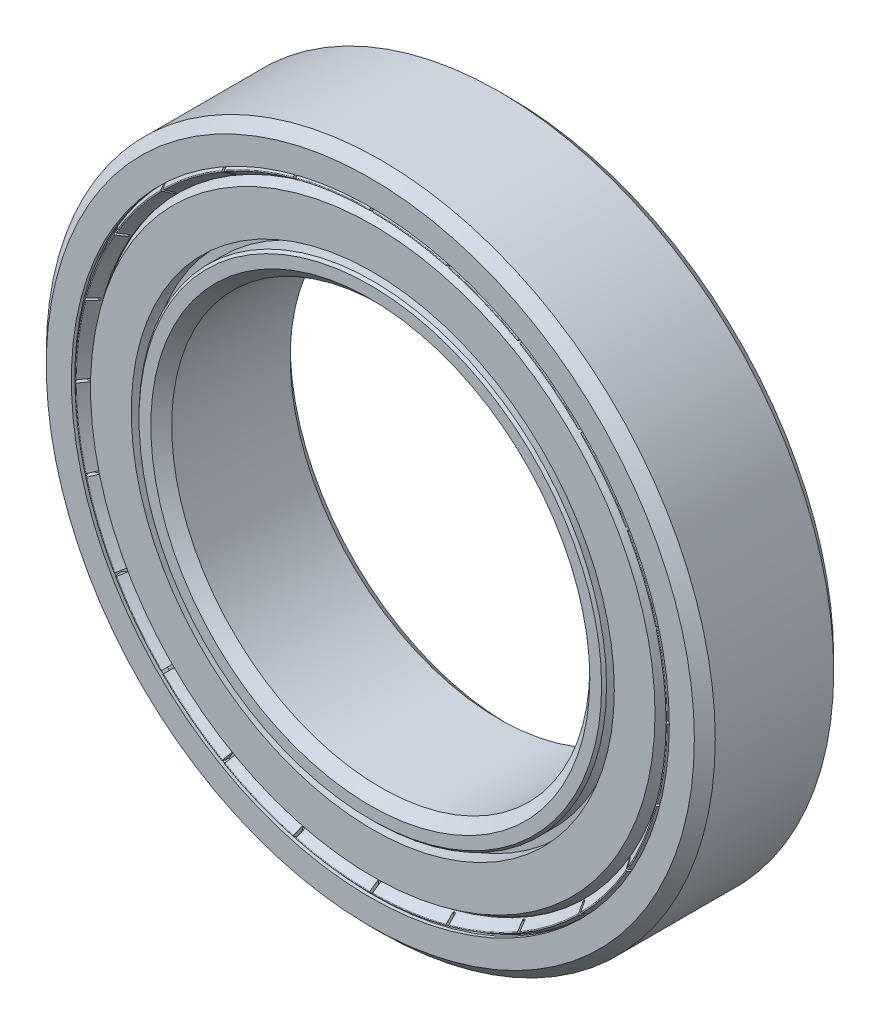
SolidWorks part; units mm, degrees
ref_plane "Front Plane" through (0, 0, 0) normal (0, 0, 1) x (1, 0, 0)
ref_plane "Top Plane" through (0, 0, 0) normal (0, 1, 0) x (1, 0, 0)
ref_plane "Right Plane" through (0, 0, 0) normal (1, 0, 0) x (0, 0, -1)
sketch "Sketch1" plane through (0, 0, 0) normal (0, 0, 1) x (1, 0, 0)
  circle A0 centre (0, 0) radius 7.5
  circle A1 centre (0, 0) radius 12
  dimension "OD" = 24
  dimension "ID" = 15
sketch "Sketch2" plane through (0, 0, 0) normal (1, 0, 0) x (0, 0, -1)
  line L0 (-2.5, 12) -> (2.5, 12)
  line L1 (-2.5, 7.5) -> (-2.5, -7.5) construction
  line L2 (2.5, 12) -> (2.5, -12) construction
  line L3 (-2.5, 0) -> (2.5, 0) construction
  line L6 (0, 12) -> (0, 7.5) construction
  circle A0 centre (0, 9.75) radius 1.575 construction
  point P8 (0, 12)
  dimension "Approx. Ball Dia." = 3.15
  dimension "Width" = 5
  dimension "For Shaft Diameter" = 15
  dimension "For Housing ID" = 24
sketch "Sketch3" plane through (0, 0, 0) normal (1, 0, 0) x (0, 0, -1)
  line L0 (0, 0) -> (0, 15) construction
  line L1 (-2.5, 7.5) -> (-2.5, -7.5) construction
  line L2 (2.125, 12) -> (-2.125, 12)
  line L3 (-2.125, 12) -> (-2.5, 11.625)
  line L4 (-2.5, 11.625) -> (-2.5, 10.7262)
  line L5 (-2.5, 10.7262) -> (-2.375, 10.7262)
  line L6 (-2.375, 10.7262) -> (-2.375, 11.0256)
  line L7 (-2.375, 11.0256) -> (-2.2866, 11.114)
  line L8 (-2.2866, 11.114) -> (-0.7875, 11.114)
  line L10 (-2.5, 12) -> (2.5, 12) construction
  line L12 (-2.375, 11.0256) -> (-2.375, 11.325) construction
  line L13 (2.2866, 11.114) -> (0.7875, 11.114)
  line L14 (2.375, 11.0256) -> (2.2866, 11.114)
  line L15 (2.375, 10.7262) -> (2.375, 11.0256)
  line L16 (2.5, 10.7262) -> (2.375, 10.7262)
  line L17 (2.5, 11.625) -> (2.5, 10.7262)
  line L18 (2.125, 12) -> (2.5, 11.625)
  line L19 (2.125, 7.5) -> (-2.125, 7.5)
  line L20 (-2.125, 7.5) -> (-2.5, 7.875)
  line L21 (-2.5, 7.875) -> (-2.5, 8.2976)
  line L22 (-2.5, 8.2976) -> (-2.4116, 8.386)
  line L23 (-2.4116, 8.386) -> (-0.7875, 8.386)
  line L25 (2.4116, 8.386) -> (0.7875, 8.386)
  line L26 (2.5, 8.2976) -> (2.4116, 8.386)
  line L27 (2.5, 7.875) -> (2.5, 8.2976)
  line L28 (2.125, 7.5) -> (2.5, 7.875)
  circle A2 centre (0, 9.75) radius 1.575 construction
  arc A3 (-0.7875, 11.114) -> (0.7875, 11.114) centre (0, 9.75) cw
  arc A4 (-0.7875, 8.386) -> (0.7875, 8.386) centre (0, 9.75) ccw
  point P5 (0, 11.325)
  point P31 (0, 12)
  point P37 (0, 7.5)
  dimension "D1" = 45
  dimension "D2" = 0.125
  dimension "D3" = 1.575
  dimension "D4" = 0.375
revolve "Revolve1" add sketch "Sketch3" angle 360 about L3
sketch "Sketch4" plane through (0, 0, 0) normal (1, 0, 0) x (0, 0, -1)
  line L0 (0, 11.325) -> (0, 8.175)
  line L1 (0, 12) -> (0, 7.5) construction
  circle A0 centre (0, 9.75) radius 1.575 construction
  arc A1 (0, 8.175) -> (0, 11.325) centre (0, 9.75) cw
revolve "Revolve2" add sketch "Sketch4" angle 360 about L6
pattern_circular "CirPattern1" count 12 over 360 about axis through (0, 0, 0) along (0, 0, 1) of bodies 106
sketch "Sketch5" plane through (0, 0, 0) normal (1, 0, 0) x (0, 0, -1)
  line L0 (-1.575, 9.75) -> (-1.575, 8.386) construction
  line L1 (-2.4116, 8.386) -> (-0.7875, 8.386) construction
  line L3 (-1.575, 8.386) -> (-1.8539, 8.386)
  line L4 (-1.8539, 8.386) -> (-1.8539, 8.6649)
  line L5 (-1.8539, 8.6649) -> (-2.4116, 8.6649)
  line L6 (-2.4116, 8.6649) -> (-2.4116, 10.1253)
  line L7 (-2.4116, 10.1253) -> (-1.8539, 10.4473)
  line L8 (-1.8539, 10.4473) -> (-1.575, 10.4473)
  line L9 (-1.575, 10.4473) -> (-1.575, 8.386)
  line L10 (0, 9.75) -> (0, 12) construction
  line L11 (1.8539, 10.4473) -> (1.575, 10.4473)
  line L12 (2.4116, 10.1253) -> (1.8539, 10.4473)
  line L13 (2.4116, 8.6649) -> (2.4116, 10.1253)
  line L14 (1.8539, 8.6649) -> (2.4116, 8.6649)
  line L15 (1.8539, 8.386) -> (1.8539, 8.6649)
  line L16 (1.575, 8.386) -> (1.8539, 8.386)
  line L17 (1.575, 10.4473) -> (1.575, 8.386)
  line L18 (-2.4116, 10.1253) -> (-2.1327, 10.1253) construction
  line L19 (-2.1327, 10.1253) -> (-1.8539, 10.1253) construction
  line L20 (-1.8539, 10.1253) -> (-1.575, 10.1253) construction
  line L21 (-1.8539, 10.4473) -> (-1.8539, 10.7262) construction
  circle A0 centre (0, 9.75) radius 1.575 construction
  dimension "D1" = 30
revolve "Revolve3" add sketch "Sketch5" angle 360 about L3
sketch "Sketch6" plane through (0, 0, 0) normal (1, 0, 0) x (0, 0, -1)
  line L0 (-2.0406, 10.7262) -> (-2.2812, 10.7262)
  line L1 (-2.2812, 10.7262) -> (-2.5, 10.5999)
  line L2 (-2.5, 10.5999) -> (-2.1156, 10.3307)
  line L4 (-2.4116, 10.1253) -> (-1.8539, 10.4473) construction
  line L5 (-2.0406, 10.3395) -> (-2.0406, 10.7262)
  line L6 (-2.5, 10.7262) -> (-2.375, 10.7262) construction
  line L7 (-2.1156, 10.3307) -> (-2.0906, 10.3307)
  line L8 (-2.0906, 10.3307) -> (-2.0406, 10.3395)
  line L9 (-2.5, 11.625) -> (-2.5, -11.625) construction
  line L11 (-2.0906, 10.3307) -> (-2.0656, 10.3307) construction
  line L12 (-2.0656, 10.3307) -> (-2.0406, 10.3307) construction
  point P27 (-2.1609, 10.7262)
  dimension "D1" = 30
  dimension "D3" = 10
  dimension "D2" = 35
  dimension "D4" = 0.025
  dimension "D5" = 0.2188
revolve "Revolve4" add sketch "Sketch6" angle 360 about L3
fillet "Fillet1" radius 0.025 1 edges at (10.5999, 0, 2.5)
sketch "Sketch7" plane through (0, 0, 0) normal (0, 0, 1) x (1, 0, 0)
  line L0 (-0.05, 10.7262) -> (-0.05, 10.8262)
  line L1 (-0.05, 10.7262) -> (0.05, 10.7262) construction
  line L2 (-0.05, 10.7262) -> (-0.05, 10.3307)
  line L3 (-0.05, 10.3307) -> (0.05, 10.3307) construction
  line L4 (0.05, 10.7262) -> (0.05, 10.3307)
  line L5 (-0.05, 10.8262) -> (0.05, 10.8262)
  line L6 (0.05, 10.8262) -> (0.05, 10.7262)
  line L7 (-0.05, 10.3307) -> (-0.05, 10.2307)
  line L8 (-0.05, 10.2307) -> (0.05, 10.2307)
  line L9 (0.05, 10.2307) -> (0.05, 10.3307)
  dimension "D1" = 0.1
extrude "Cut-Extrude1" cut sketch "Sketch7" along normal through all from vertex at 2.1609 starting at point (0, 10.7262, 2.1609)
pattern_circular "CirPattern2" count 24 over 360 about axis through (0, 0, 0) along (0, 0, 1) of "Cut-Extrude1"
mirror "Mirror1" about plane through (0, 0, 0) normal (0, 0, 1) of bodies 120
equation "\"Approx. Ball Dia.@Sketch2\"=( \"OD@Sketch1\" - \"ID@Sketch1\" )  * .5 * .7"
equation "\"D2@Sketch3\"=\"Width@Sketch2\"*.025"
equation "\"D3@Sketch3\"=\"Approx. Ball Dia.@Sketch2\"*.5"
equation "\"D4@Sketch3\"=\"Width@Sketch2\"*.075"
equation "\"Approx No of Balls\"= ( pi * \"OD@Sketch1\" ) * .5 / \"Approx. Ball Dia.@Sketch2\""
equation "\"D1@CirPattern1\"=\"Approx No of Balls\""
equation "\"D4@Sketch6\"=\"D2@Sketch3\"*.2"
equation "\"D1@CirPattern2\"=\"Approx No of Balls\"*2"
equation "\"D5@Sketch6\"=\"D2@Sketch3\"*1.75"
equation "\"D1@Fillet1\"=\"d4@sketch6\""
